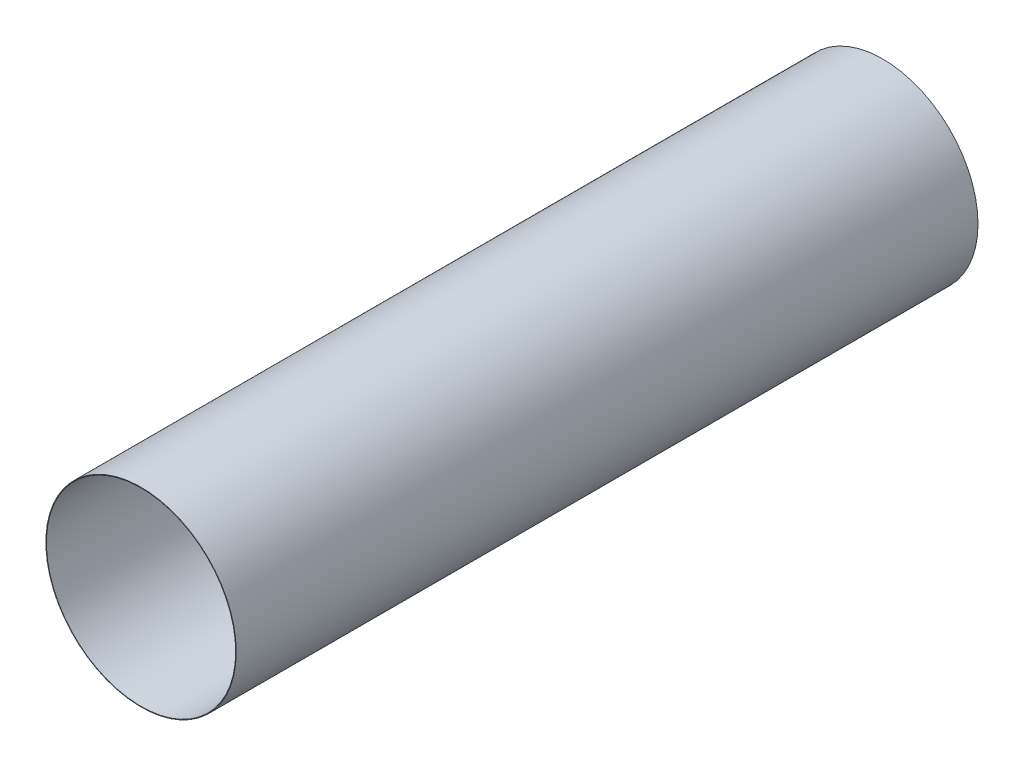
SolidWorks part; units mm, degrees
ref_plane "Front Plane" through (0, 0, 0) normal (0, 0, 1) x (1, 0, 0)
ref_plane "Top Plane" through (0, 0, 0) normal (0, 1, 0) x (1, 0, 0)
ref_plane "Right Plane" through (0, 0, 0) normal (1, 0, 0) x (0, 0, -1)
ref_axis "Axis1" through (0, 0, 754.38) along (0, 0, -1)
sketch "Sketch2" plane through (0, 0, 0) normal (1, 0, 0) x (0, 0, -1)
  line L1 (-590.55, 150.7451) -> (590.55, 150.7451)
  line L2 (-590.55, 150.7451) -> (-590.55, 151.5951)
  line L3 (-590.55, 151.5951) -> (590.55, 151.5951)
  line L4 (590.55, 150.7451) -> (590.55, 151.5951)
  point P4 (0, 0)
  point P8 (0, 150.7451)
  dimension "D1" = 1181.1
  dimension "D2" = 0.85
  dimension "D3" = 151.5951
revolve "Revolve1" add sketch "Sketch2" angle 360 about axis through (0, 0, 754.38) along (0, 0, -1)
